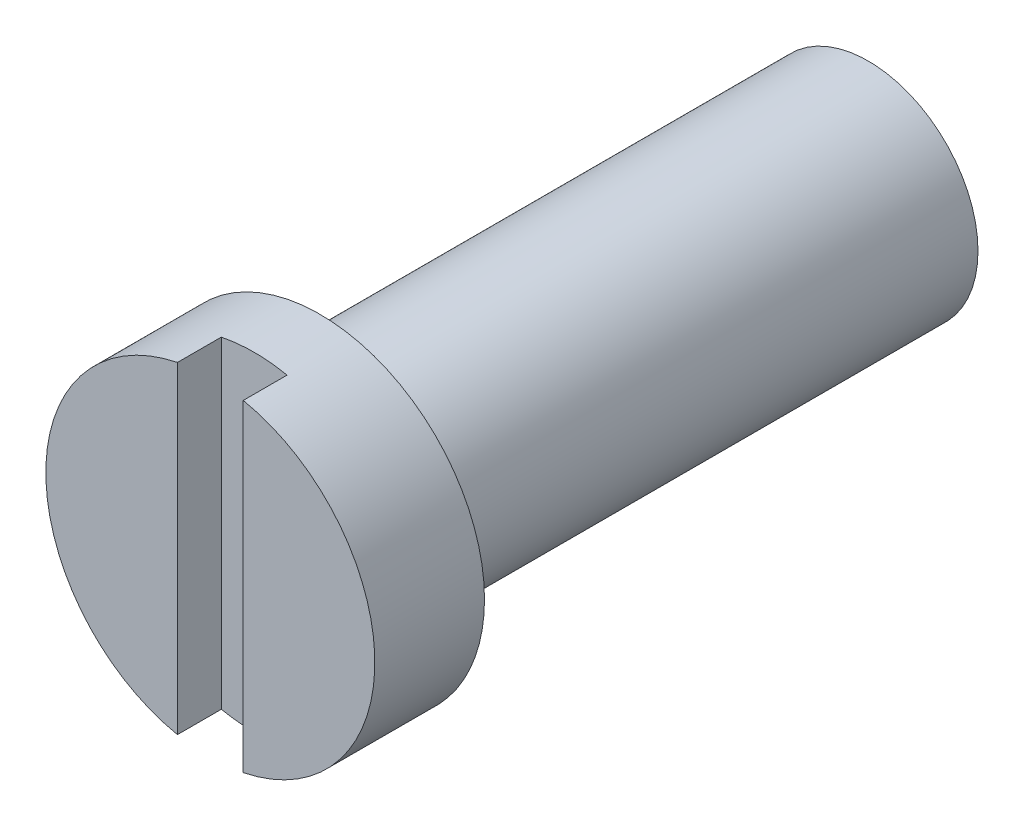
SolidWorks part; units mm, degrees
ref_plane "Front Plane" through (0, 0, 0) normal (0, 0, 1) x (1, 0, 0)
ref_plane "Top Plane" through (0, 0, 0) normal (0, 1, 0) x (1, 0, 0)
ref_plane "Right Plane" through (0, 0, 0) normal (1, 0, 0) x (0, 0, -1)
sketch "Sketch1" plane through (0, 0, 0) normal (0, 0, 1) x (1, 0, 0)
  circle A0 centre (0, 0) radius 0.5
  dimension "D1" = 1
extrude "Boss-Extrude1" add sketch "Sketch1" along normal blind 2.5
sketch "Sketch2" plane through (0, 0, 2.5) normal (0, 0, 1) x (1, 0, 0)
  circle A0 centre (0, 0) radius 0.75
  dimension "D1" = 1.5
extrude "Boss-Extrude2" add sketch "Sketch2" along normal blind 0.5
sketch "Sketch3" plane through (0, 0, 3) normal (0, 0, 1) x (1, 0, 0)
  line L0 (0, -0.75) -> (0, 0.75) construction
  line L1 (0.15, 0.7348) -> (0.15, -0.7348)
  line L2 (-0.15, 0.7348) -> (-0.15, -0.7348)
  circle A0 centre (0, 0) radius 0.75 construction
  arc A1 (-0.15, -0.7348) -> (0.15, -0.7348) centre (0, 0) ccw
  arc A2 (0.15, 0.7348) -> (-0.15, 0.7348) centre (0, 0) ccw
  dimension "D1" = 0.15
extrude "Cut-Extrude1" cut sketch "Sketch3" against normal blind 0.2
